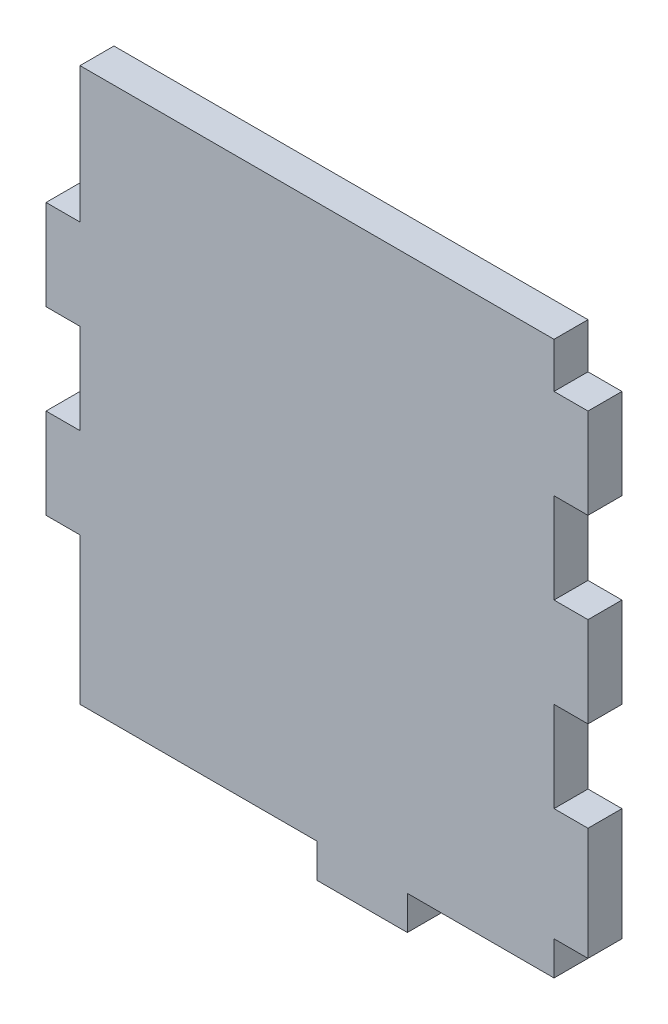
SolidWorks part; units mm, degrees
ref_plane "Front Plane" through (0, 0, 0) normal (0, 0, 1) x (1, 0, 0)
ref_plane "Top Plane" through (0, 0, 0) normal (0, 1, 0) x (1, 0, 0)
ref_plane "Right Plane" through (0, 0, 0) normal (1, 0, 0) x (0, 0, -1)
sketch "Sketch2" plane through (0, 0, 0) normal (0, 0, 1) x (1, 0, 0)
  line L1 (0, 0) -> (76.2, 0)
  line L2 (0, 0) -> (0, 82.55)
  line L3 (0, 82.55) -> (76.2, 82.55)
  line L4 (76.2, 0) -> (76.2, 82.55)
  dimension "D1" = 76.2
  dimension "D2" = 82.55
extrude "Boss-Extrude1" add sketch "Sketch2" along normal blind 4.7752
sketch "Sketch3" plane through (0, 0, 4.7752) normal (0, 0, 1) x (1, 0, 0)
  line L0 (0, 0) -> (76.2, 0) construction
  line L1 (0, 82.55) -> (0, 0) construction
  line L2 (38.1, 0) -> (0, 0)
  line L3 (38.1, 0) -> (38.1, 4.7752)
  line L4 (38.1, 4.7752) -> (0, 4.7752)
  line L5 (0, 0) -> (0, 4.7752)
  line L7 (38.1, 0) -> (50.8, 0)
  line L8 (38.1, 0) -> (38.1, 4.7752)
  line L9 (38.1, 4.7752) -> (50.8, 4.7752)
  line L10 (50.8, 0) -> (50.8, 4.7752)
  line L11 (50.8, 4.7752) -> (76.2, 4.7752)
  line L12 (50.8, 4.7752) -> (50.8, 0)
  line L13 (50.8, 0) -> (76.2, 0)
  line L14 (76.2, 4.7752) -> (76.2, 0)
  line M5 (0, 82.55) -> (0, 0)
  line M6 (0, 0) -> (76.2, 0)
  line M7 (76.2, 0) -> (76.2, 82.55)
  dimension "D1" = 4.7752
  dimension "D2" = 12.7
extrude "Cut-Extrude1" cut sketch "Sketch3" against normal blind 4.7752 contours L3 L4 M5 M6 | L11 L10 M6 M7
sketch "Sketch4" plane through (0, 0, 4.7752) normal (0, 0, 1) x (1, 0, 0)
  line L1 (0, 4.7752) -> (4.7752, 4.7752)
  line L2 (0, 4.7752) -> (0, 25.4)
  line L3 (0, 25.4) -> (4.7752, 25.4)
  line L4 (4.7752, 4.7752) -> (4.7752, 25.4)
  line L5 (0, 25.4) -> (4.7752, 25.4)
  line L6 (0, 25.4) -> (0, 38.1)
  line L7 (0, 38.1) -> (4.7752, 38.1)
  line L8 (4.7752, 25.4) -> (4.7752, 38.1)
  line L9 (0, 38.1) -> (4.7752, 38.1)
  line L10 (0, 38.1) -> (0, 50.8)
  line L11 (0, 50.8) -> (4.7752, 50.8)
  line L12 (4.7752, 38.1) -> (4.7752, 50.8)
  line L13 (0, 50.8) -> (4.7752, 50.8)
  line L14 (0, 50.8) -> (0, 63.5)
  line L15 (0, 63.5) -> (4.7752, 63.5)
  line L16 (4.7752, 50.8) -> (4.7752, 63.5)
  line L17 (76.2, 82.55) -> (0, 82.55) construction
  line L18 (0, 63.5) -> (4.7752, 63.5)
  line L19 (0, 63.5) -> (0, 82.55)
  line L20 (0, 82.55) -> (4.7752, 82.55)
  line L21 (4.7752, 63.5) -> (4.7752, 82.55)
  line M7 (0, 4.7752) -> (38.1, 4.7752)
  line M13 (76.2, 82.55) -> (0, 82.55)
  line M14 (0, 82.55) -> (0, 4.7752)
  dimension "D1" = 20.6248
  dimension "D2" = 4.7752
  dimension "D3" = 19.05
  dimension "D4" = 12.7
  dimension "D5" = 12.7
extrude "Cut-Extrude2" cut sketch "Sketch4" against normal blind 4.7752 contours L15 L21 M13 M14 | L7 L12 L11 M14 | L4 L3 M7 M14
sketch "Sketch5" plane through (0, 0, 4.7752) normal (0, 0, 1) x (1, 0, 0)
  line L0 (76.2, 82.55) -> (4.7752, 82.55) construction
  line L1 (76.2, 4.7752) -> (71.4248, 4.7752)
  line L2 (76.2, 4.7752) -> (76.2, 9.5504)
  line L3 (76.2, 9.5504) -> (71.4248, 9.5504)
  line L4 (71.4248, 4.7752) -> (71.4248, 9.5504)
  line L5 (76.2, 9.5504) -> (71.4248, 9.5504)
  line L6 (76.2, 9.5504) -> (76.2, 25.4)
  line L7 (76.2, 25.4) -> (71.4248, 25.4)
  line L8 (71.4248, 9.5504) -> (71.4248, 25.4)
  line L9 (76.2, 25.4) -> (71.4248, 25.4)
  line L10 (76.2, 25.4) -> (76.2, 38.1)
  line L11 (76.2, 38.1) -> (71.4248, 38.1)
  line L12 (71.4248, 25.4) -> (71.4248, 38.1)
  line L13 (76.2, 38.1) -> (71.4248, 38.1)
  line L14 (76.2, 38.1) -> (76.2, 50.8)
  line L15 (76.2, 50.8) -> (71.4248, 50.8)
  line L16 (71.4248, 38.1) -> (71.4248, 50.8)
  line L17 (76.2, 50.8) -> (71.4248, 50.8)
  line L18 (76.2, 50.8) -> (76.2, 63.5)
  line L19 (76.2, 63.5) -> (71.4248, 63.5)
  line L20 (71.4248, 50.8) -> (71.4248, 63.5)
  line L21 (76.2, 63.5) -> (71.4248, 63.5)
  line L22 (76.2, 63.5) -> (76.2, 76.2)
  line L23 (76.2, 76.2) -> (71.4248, 76.2)
  line L24 (71.4248, 63.5) -> (71.4248, 76.2)
  line L25 (76.2, 76.2) -> (71.4248, 76.2)
  line L26 (76.2, 76.2) -> (76.2, 82.55)
  line L27 (76.2, 82.55) -> (71.4248, 82.55)
  line L28 (71.4248, 76.2) -> (71.4248, 82.55)
  line M22 (50.8, 4.7752) -> (76.2, 4.7752)
  line M23 (76.2, 4.7752) -> (76.2, 82.55)
  line M24 (76.2, 82.55) -> (4.7752, 82.55)
  dimension "D1" = 4.7752
  dimension "D2" = 4.7752
  dimension "D3" = 15.8496
  dimension "D4" = 6.35
  dimension "D5" = 12.7
  dimension "D6" = 12.7
  dimension "D7" = 12.7
extrude "Cut-Extrude3" cut sketch "Sketch5" against normal blind 4.7752 contours L4 L3 M22 M23 | L12 L7 L11 M23 | L20 L15 L19 M23 | L28 L23 M23 M24
